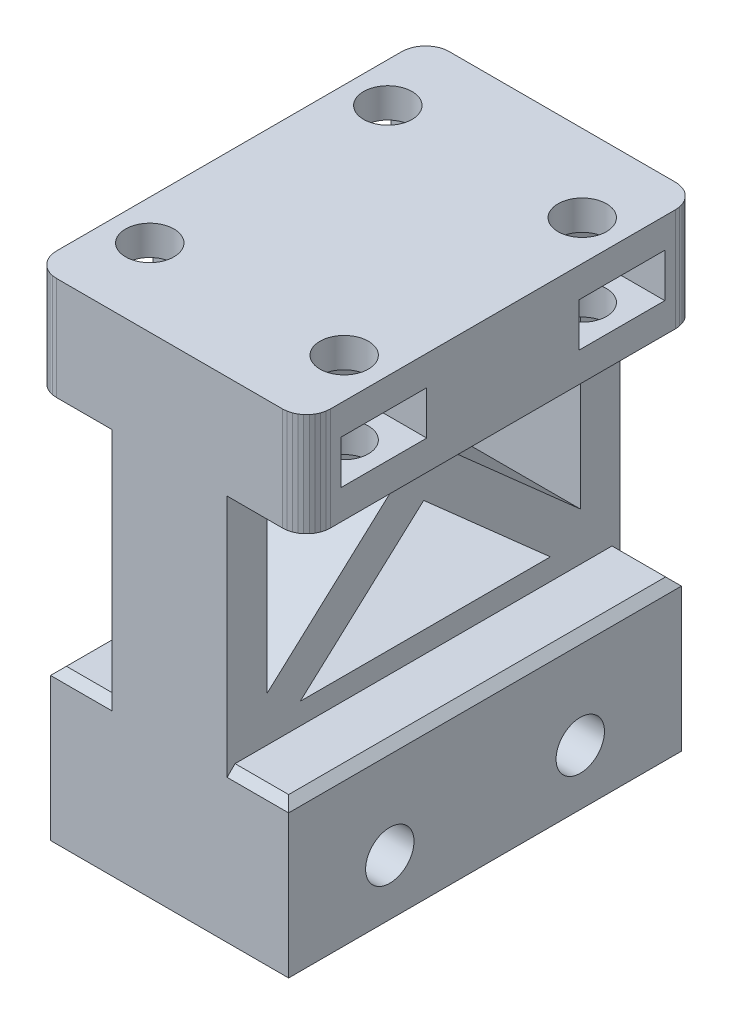
SolidWorks part; units mm, degrees
ref_plane "Front Plane" through (0, 0, 0) normal (0, 0, 1) x (1, 0, 0)
ref_plane "Top Plane" through (0, 0, 0) normal (0, 1, 0) x (1, 0, 0)
ref_plane "Right Plane" through (0, 0, 0) normal (1, 0, 0) x (0, 0, -1)
ref_plane "Plane1" through (652.0422, 0, 0) normal (-1, 0, 0) x (0, -1, 0)
sketch "Sketch1" plane through (652.0422, 0, 0) normal (-1, 0, 0) x (0, -1, 0)
  line L0 (-861.9581, 1249.6927) -> (-861.9581, 1289.1927)
  line L1 (-861.9581, 1289.1927) -> (-876.5101, 1273.1855)
  line L2 (-876.5101, 1273.1855) -> (-886.034, 1283.9338)
  line L3 (-886.034, 1283.9338) -> (-886.034, 1255.2762)
  line L4 (-886.034, 1255.2762) -> (-876.5578, 1265.7)
  line L5 (-876.5578, 1265.7) -> (-862.3742, 1249.6927)
  line L6 (-862.3742, 1249.6927) -> (-861.9581, 1249.6927)
extrude "Boss-Extrude1" add sketch "Sketch1" against normal blind 14.5
sketch "Sketch2" plane through (0, 861.9581, 0) normal (0, -1, 0) x (1, 0, 0)
  line L0 (652.0422, 1249.6927) -> (652.0422, 1289.1927)
  line L1 (652.0422, 1289.1927) -> (666.5421, 1289.1927)
  line L2 (666.5421, 1289.1927) -> (666.5421, 1249.6927)
  line L3 (666.5421, 1249.6927) -> (652.0422, 1249.6927)
extrude "Boss-Extrude2" add sketch "Sketch2" along normal blind 25.6425
sketch "Sketch3" plane through (0, 0, 1249.6927) normal (0, 0, -1) x (-1, 0, 0)
  line L0 (-652.0422, 886.034) -> (-652.0422, 836.3156)
  line L1 (-652.0422, 836.3156) -> (-666.5421, 836.3156)
  line L2 (-666.5421, 836.3156) -> (-666.5421, 886.034)
  line L3 (-666.5421, 886.034) -> (-652.0422, 886.034)
extrude "Boss-Extrude3" add sketch "Sketch3" along normal blind 5
sketch "Sketch4" plane through (0, 0, 1289.1927) normal (0, 0, 1) x (1, 0, 0)
  line L0 (652.0422, 886.034) -> (666.5421, 886.034)
  line L1 (666.5421, 886.034) -> (666.5421, 836.3156)
  line L2 (666.5421, 836.3156) -> (652.0422, 836.3156)
  line L3 (652.0422, 836.3156) -> (652.0422, 886.034)
extrude "Boss-Extrude4" add sketch "Sketch4" along normal blind 5
sketch "Sketch5" plane through (0, 886.034, 0) normal (0, 1, 0) x (-1, 0, 0)
  line L0 (-642.744, 1245.7644) -> (-643.1137, 1245.3946)
  line L1 (-643.1137, 1245.3946) -> (-643.5421, 1245.0947)
  line L2 (-643.5421, 1245.0947) -> (-644.0161, 1244.8736)
  line L3 (-644.0161, 1244.8736) -> (-644.5212, 1244.7383)
  line L4 (-644.5212, 1244.7383) -> (-645.0421, 1244.6927)
  line L5 (-645.0421, 1244.6927) -> (-673.5421, 1244.6927)
  line L6 (-673.5421, 1244.6927) -> (-674.0631, 1244.7383)
  line L7 (-674.0631, 1244.7383) -> (-674.5682, 1244.8736)
  line L8 (-674.5682, 1244.8736) -> (-675.0422, 1245.0947)
  line L9 (-675.0422, 1245.0947) -> (-675.4705, 1245.3946)
  line L10 (-675.4705, 1245.3946) -> (-675.8403, 1245.7644)
  line L11 (-675.8403, 1245.7644) -> (-676.1402, 1246.1927)
  line L12 (-676.1402, 1246.1927) -> (-676.3612, 1246.6667)
  line L13 (-676.3612, 1246.6667) -> (-676.4966, 1247.1718)
  line L14 (-676.4966, 1247.1718) -> (-676.5421, 1247.6927)
  line L15 (-676.5421, 1247.6927) -> (-676.5421, 1291.1927)
  line L16 (-676.5421, 1291.1927) -> (-676.4966, 1291.7136)
  line L17 (-676.4966, 1291.7136) -> (-676.3612, 1292.2187)
  line L18 (-676.3612, 1292.2187) -> (-676.1402, 1292.6927)
  line L19 (-676.1402, 1292.6927) -> (-675.8403, 1293.1211)
  line L20 (-675.8403, 1293.1211) -> (-675.4705, 1293.4908)
  line L21 (-675.4705, 1293.4908) -> (-675.0422, 1293.7908)
  line L22 (-675.0422, 1293.7908) -> (-674.5682, 1294.0117)
  line L23 (-674.5682, 1294.0117) -> (-674.0631, 1294.1471)
  line L24 (-674.0631, 1294.1471) -> (-673.5421, 1294.1927)
  line L25 (-673.5421, 1294.1927) -> (-645.0421, 1294.1927)
  line L26 (-645.0421, 1294.1927) -> (-644.5212, 1294.1471)
  line L27 (-644.5212, 1294.1471) -> (-644.0161, 1294.0117)
  line L28 (-644.0161, 1294.0117) -> (-643.5421, 1293.7908)
  line L29 (-643.5421, 1293.7908) -> (-643.1137, 1293.4908)
  line L30 (-643.1137, 1293.4908) -> (-642.744, 1293.1211)
  line L31 (-642.744, 1293.1211) -> (-642.4441, 1292.6927)
  line L32 (-642.4441, 1292.6927) -> (-642.2231, 1292.2187)
  line L33 (-642.2231, 1292.2187) -> (-642.0877, 1291.7136)
  line L34 (-642.0877, 1291.7136) -> (-642.0421, 1291.1927)
  line L35 (-642.0421, 1291.1927) -> (-642.0421, 1247.6927)
  line L36 (-642.0421, 1247.6927) -> (-642.0877, 1247.1718)
  line L37 (-642.0877, 1247.1718) -> (-642.2231, 1246.6667)
  line L38 (-642.2231, 1246.6667) -> (-642.4441, 1246.1927)
  line L39 (-642.4441, 1246.1927) -> (-642.744, 1245.7644)
extrude "Boss-Extrude5" add sketch "Sketch5" along normal blind 13
sketch "Sketch6" plane through (652.0422, 0, 0) normal (-1, 0, 0) x (0, 0, 1)
  line L0 (1244.6927, 836.3156) -> (1244.6927, 856.334)
  line L1 (1244.6927, 856.334) -> (1294.1927, 856.334)
  line L2 (1294.1927, 856.334) -> (1294.1927, 836.3156)
  line L3 (1294.1927, 836.3156) -> (1244.6927, 836.3156)
extrude "Boss-Extrude6" add sketch "Sketch6" along normal blind 7.75
sketch "Sketch7" plane through (666.5421, 0, 0) normal (1, 0, 0) x (0, 0, -1)
  line L0 (-1294.1927, 836.3156) -> (-1294.1927, 856.334)
  line L1 (-1294.1927, 856.334) -> (-1244.6927, 856.334)
  line L2 (-1244.6927, 856.334) -> (-1244.6927, 836.3156)
  line L3 (-1244.6927, 836.3156) -> (-1294.1927, 836.3156)
extrude "Boss-Extrude7" add sketch "Sketch7" along normal blind 7.75
ref_plane "Plane2" through (0, 889.784, 0) normal (0, -1, 0) x (1, 0, 0)
sketch "Sketch8" plane through (0, 889.784, 0) normal (0, -1, 0) x (1, 0, 0)
  line L0 (676.5421, 1259.8467) -> (668.4221, 1259.8467)
  line L1 (668.4221, 1259.8467) -> (665.3021, 1254.4427)
  line L2 (665.3021, 1254.4427) -> (668.4221, 1249.0387)
  line L3 (668.4221, 1249.0387) -> (676.5421, 1249.0387)
  line L4 (676.5421, 1249.0387) -> (676.5421, 1259.8467)
extrude "Cut-Extrude1" cut sketch "Sketch8" against normal blind 5.5
sketch "Sketch9" plane through (0, 899.034, 0) normal (0, 1, 0) x (-1, 0, 0)
  line L0 (-672.0718, 1251.439) -> (-671.5421, 1251.3927) construction
  line L1 (-671.5421, 1251.3927) -> (-671.0125, 1251.439) construction
  line L2 (-671.0125, 1251.439) -> (-670.499, 1251.5767) construction
  line L3 (-670.499, 1251.5767) -> (-670.0171, 1251.8013) construction
  line L4 (-670.0171, 1251.8013) -> (-669.5817, 1252.1062) construction
  line L5 (-669.5817, 1252.1062) -> (-669.2057, 1252.4822) construction
  line L6 (-669.2057, 1252.4822) -> (-668.9007, 1252.9176) construction
  line L7 (-668.9007, 1252.9176) -> (-668.6761, 1253.3995) construction
  line L8 (-668.6761, 1253.3995) -> (-668.5385, 1253.913) construction
  line L9 (-668.5385, 1253.913) -> (-668.4921, 1254.4427) construction
  line L10 (-668.4921, 1254.4427) -> (-668.5385, 1254.9723) construction
  line L11 (-668.5385, 1254.9723) -> (-668.6761, 1255.4859) construction
  line L12 (-668.6761, 1255.4859) -> (-668.9007, 1255.9677) construction
  line L13 (-668.9007, 1255.9677) -> (-669.2057, 1256.4032) construction
  line L14 (-669.2057, 1256.4032) -> (-669.5817, 1256.7791) construction
  line L15 (-669.5817, 1256.7791) -> (-670.0171, 1257.084) construction
  line L16 (-670.0171, 1257.084) -> (-670.499, 1257.3087) construction
  line L17 (-670.499, 1257.3087) -> (-671.0125, 1257.4463) construction
  line L18 (-671.0125, 1257.4463) -> (-671.5421, 1257.4927) construction
  line L19 (-671.5421, 1257.4927) -> (-672.0718, 1257.4463) construction
  line L20 (-672.0718, 1257.4463) -> (-672.5853, 1257.3087) construction
  line L21 (-672.5853, 1257.3087) -> (-673.0672, 1257.084) construction
  line L22 (-673.0672, 1257.084) -> (-673.5026, 1256.7791) construction
  line L23 (-673.5026, 1256.7791) -> (-673.8786, 1256.4032) construction
  line L24 (-673.8786, 1256.4032) -> (-674.1835, 1255.9677) construction
  line L25 (-674.1835, 1255.9677) -> (-674.4082, 1255.4859) construction
  line L26 (-674.4082, 1255.4859) -> (-674.5458, 1254.9723) construction
  line L27 (-674.5458, 1254.9723) -> (-674.5921, 1254.4427) construction
  line L28 (-674.5921, 1254.4427) -> (-674.5458, 1253.913) construction
  line L29 (-674.5458, 1253.913) -> (-674.4082, 1253.3995) construction
  line L30 (-674.4082, 1253.3995) -> (-674.1835, 1252.9176) construction
  line L31 (-674.1835, 1252.9176) -> (-673.8786, 1252.4822) construction
  line L32 (-673.8786, 1252.4822) -> (-673.5026, 1252.1062) construction
  line L33 (-673.5026, 1252.1062) -> (-673.0672, 1251.8013) construction
  line L34 (-673.0672, 1251.8013) -> (-672.5853, 1251.5767) construction
  line L35 (-672.5853, 1251.5767) -> (-672.0718, 1251.439) construction
  line L36 (-671.5421, 1251.3927) -> (-671.5421, 1257.4927) construction
  circle A0 centre (-671.5421, 1254.4427) radius 3.05
extrude "Cut-Extrude2" cut sketch "Sketch9" against normal up to surface (13 mm away)
sketch "Sketch10" plane through (0, 889.784, 0) normal (0, -1, 0) x (1, 0, 0)
  line L0 (642.0421, 1249.0387) -> (650.1621, 1249.0387)
  line L1 (650.1621, 1249.0387) -> (653.2821, 1254.4427)
  line L2 (653.2821, 1254.4427) -> (650.1621, 1259.8467)
  line L3 (650.1621, 1259.8467) -> (642.0421, 1259.8467)
  line L4 (642.0421, 1259.8467) -> (642.0421, 1249.0387)
extrude "Cut-Extrude3" cut sketch "Sketch10" against normal blind 5.5
sketch "Sketch11" plane through (0, 899.034, 0) normal (0, 1, 0) x (-1, 0, 0)
  line L0 (-647.5717, 1257.4463) -> (-648.0852, 1257.3087) construction
  line L1 (-648.0852, 1257.3087) -> (-648.5671, 1257.084) construction
  line L2 (-648.5671, 1257.084) -> (-649.0026, 1256.7791) construction
  line L3 (-649.0026, 1256.7791) -> (-649.3785, 1256.4032) construction
  line L4 (-649.3785, 1256.4032) -> (-649.6835, 1255.9677) construction
  line L5 (-649.6835, 1255.9677) -> (-649.9082, 1255.4859) construction
  line L6 (-649.9082, 1255.4859) -> (-650.0458, 1254.9723) construction
  line L7 (-650.0458, 1254.9723) -> (-650.0921, 1254.4427) construction
  line L8 (-650.0921, 1254.4427) -> (-650.0458, 1253.913) construction
  line L9 (-650.0458, 1253.913) -> (-649.9082, 1253.3995) construction
  line L10 (-649.9082, 1253.3995) -> (-649.6835, 1252.9176) construction
  line L11 (-649.6835, 1252.9176) -> (-649.3785, 1252.4822) construction
  line L12 (-649.3785, 1252.4822) -> (-649.0026, 1252.1062) construction
  line L13 (-649.0026, 1252.1062) -> (-648.5671, 1251.8013) construction
  line L14 (-648.5671, 1251.8013) -> (-648.0852, 1251.5767) construction
  line L15 (-648.0852, 1251.5767) -> (-647.5717, 1251.439) construction
  line L16 (-647.5717, 1251.439) -> (-647.0421, 1251.3927) construction
  line L17 (-647.0421, 1251.3927) -> (-646.5125, 1251.439) construction
  line L18 (-646.5125, 1251.439) -> (-645.999, 1251.5767) construction
  line L19 (-645.999, 1251.5767) -> (-645.5171, 1251.8013) construction
  line L20 (-645.5171, 1251.8013) -> (-645.0816, 1252.1062) construction
  line L21 (-645.0816, 1252.1062) -> (-644.7057, 1252.4822) construction
  line L22 (-644.7057, 1252.4822) -> (-644.4008, 1252.9176) construction
  line L23 (-644.4008, 1252.9176) -> (-644.1761, 1253.3995) construction
  line L24 (-644.1761, 1253.3995) -> (-644.0384, 1253.913) construction
  line L25 (-644.0384, 1253.913) -> (-643.9921, 1254.4427) construction
  line L26 (-643.9921, 1254.4427) -> (-644.0384, 1254.9723) construction
  line L27 (-644.0384, 1254.9723) -> (-644.1761, 1255.4859) construction
  line L28 (-644.1761, 1255.4859) -> (-644.4008, 1255.9677) construction
  line L29 (-644.4008, 1255.9677) -> (-644.7057, 1256.4032) construction
  line L30 (-644.7057, 1256.4032) -> (-645.0816, 1256.7791) construction
  line L31 (-645.0816, 1256.7791) -> (-645.5171, 1257.084) construction
  line L32 (-645.5171, 1257.084) -> (-645.999, 1257.3087) construction
  line L33 (-645.999, 1257.3087) -> (-646.5125, 1257.4463) construction
  line L34 (-646.5125, 1257.4463) -> (-647.0421, 1257.4927) construction
  line L35 (-647.0421, 1257.4927) -> (-647.5717, 1257.4463) construction
  line L36 (-647.0421, 1251.3927) -> (-647.0421, 1257.4927) construction
  circle A0 centre (-647.0421, 1254.4427) radius 3.05
extrude "Cut-Extrude4" cut sketch "Sketch11" against normal up to surface (13 mm away) up to face at (671.5421, 886.034, 1251.3927)
sketch "Sketch12" plane through (0, 889.784, 0) normal (0, -1, 0) x (1, 0, 0)
  line L0 (642.0421, 1279.0387) -> (650.1621, 1279.0387)
  line L1 (650.1621, 1279.0387) -> (653.2821, 1284.4427)
  line L2 (653.2821, 1284.4427) -> (650.1621, 1289.8467)
  line L3 (650.1621, 1289.8467) -> (642.0421, 1289.8467)
  line L4 (642.0421, 1289.8467) -> (642.0421, 1279.0387)
extrude "Cut-Extrude5" cut sketch "Sketch12" against normal blind 5.5
sketch "Sketch13" plane through (0, 899.034, 0) normal (0, 1, 0) x (-1, 0, 0)
  line L0 (-644.0384, 1283.913) -> (-643.9921, 1284.4427) construction
  line L1 (-643.9921, 1284.4427) -> (-644.0384, 1284.9723) construction
  line L2 (-644.0384, 1284.9723) -> (-644.1761, 1285.4859) construction
  line L3 (-644.1761, 1285.4859) -> (-644.4008, 1285.9677) construction
  line L4 (-644.4008, 1285.9677) -> (-644.7057, 1286.4032) construction
  line L5 (-644.7057, 1286.4032) -> (-645.0816, 1286.7792) construction
  line L6 (-645.0816, 1286.7792) -> (-645.5171, 1287.0841) construction
  line L7 (-645.5171, 1287.0841) -> (-645.999, 1287.3087) construction
  line L8 (-645.999, 1287.3087) -> (-646.5125, 1287.4464) construction
  line L9 (-646.5125, 1287.4464) -> (-647.0421, 1287.4926) construction
  line L10 (-647.0421, 1287.4926) -> (-647.5717, 1287.4464) construction
  line L11 (-647.5717, 1287.4464) -> (-648.0852, 1287.3087) construction
  line L12 (-648.0852, 1287.3087) -> (-648.5671, 1287.0841) construction
  line L13 (-648.5671, 1287.0841) -> (-649.0026, 1286.7792) construction
  line L14 (-649.0026, 1286.7792) -> (-649.3785, 1286.4032) construction
  line L15 (-649.3785, 1286.4032) -> (-649.6835, 1285.9677) construction
  line L16 (-649.6835, 1285.9677) -> (-649.9082, 1285.4859) construction
  line L17 (-649.9082, 1285.4859) -> (-650.0458, 1284.9723) construction
  line L18 (-650.0458, 1284.9723) -> (-650.0921, 1284.4427) construction
  line L19 (-650.0921, 1284.4427) -> (-650.0458, 1283.913) construction
  line L20 (-650.0458, 1283.913) -> (-649.9082, 1283.3995) construction
  line L21 (-649.9082, 1283.3995) -> (-649.6835, 1282.9177) construction
  line L22 (-649.6835, 1282.9177) -> (-649.3785, 1282.4821) construction
  line L23 (-649.3785, 1282.4821) -> (-649.0026, 1282.1063) construction
  line L24 (-649.0026, 1282.1063) -> (-648.5671, 1281.8013) construction
  line L25 (-648.5671, 1281.8013) -> (-648.0852, 1281.5766) construction
  line L26 (-648.0852, 1281.5766) -> (-647.5717, 1281.4391) construction
  line L27 (-647.5717, 1281.4391) -> (-647.0421, 1281.3927) construction
  line L28 (-647.0421, 1281.3927) -> (-646.5125, 1281.4391) construction
  line L29 (-646.5125, 1281.4391) -> (-645.999, 1281.5766) construction
  line L30 (-645.999, 1281.5766) -> (-645.5171, 1281.8013) construction
  line L31 (-645.5171, 1281.8013) -> (-645.0816, 1282.1063) construction
  line L32 (-645.0816, 1282.1063) -> (-644.7057, 1282.4821) construction
  line L33 (-644.7057, 1282.4821) -> (-644.4008, 1282.9177) construction
  line L34 (-644.4008, 1282.9177) -> (-644.1761, 1283.3995) construction
  line L35 (-644.1761, 1283.3995) -> (-644.0384, 1283.913) construction
  line L36 (-647.0421, 1287.4926) -> (-647.0421, 1281.3927) construction
  circle A0 centre (-647.0421, 1284.4427) radius 3.05
extrude "Cut-Extrude6" cut sketch "Sketch13" against normal up to surface (13 mm away) up to face at (647.0421, 886.034, 1251.3927)
sketch "Sketch14" plane through (0, 889.784, 0) normal (0, -1, 0) x (1, 0, 0)
  line L0 (676.5421, 1289.8467) -> (668.4221, 1289.8467)
  line L1 (668.4221, 1289.8467) -> (665.3021, 1284.4427)
  line L2 (665.3021, 1284.4427) -> (668.4221, 1279.0387)
  line L3 (668.4221, 1279.0387) -> (676.5421, 1279.0387)
  line L4 (676.5421, 1279.0387) -> (676.5421, 1289.8467)
extrude "Cut-Extrude7" cut sketch "Sketch14" against normal blind 5.5
sketch "Sketch15" plane through (0, 899.034, 0) normal (0, 1, 0) x (-1, 0, 0)
  line L0 (-673.5026, 1286.7792) -> (-673.8786, 1286.4032) construction
  line L1 (-673.8786, 1286.4032) -> (-674.1835, 1285.9677) construction
  line L2 (-674.1835, 1285.9677) -> (-674.4082, 1285.4859) construction
  line L3 (-674.4082, 1285.4859) -> (-674.5458, 1284.9723) construction
  line L4 (-674.5458, 1284.9723) -> (-674.5921, 1284.4427) construction
  line L5 (-674.5921, 1284.4427) -> (-674.5458, 1283.913) construction
  line L6 (-674.5458, 1283.913) -> (-674.4082, 1283.3995) construction
  line L7 (-674.4082, 1283.3995) -> (-674.1835, 1282.9177) construction
  line L8 (-674.1835, 1282.9177) -> (-673.8786, 1282.4821) construction
  line L9 (-673.8786, 1282.4821) -> (-673.5026, 1282.1063) construction
  line L10 (-673.5026, 1282.1063) -> (-673.0672, 1281.8013) construction
  line L11 (-673.0672, 1281.8013) -> (-672.5853, 1281.5766) construction
  line L12 (-672.5853, 1281.5766) -> (-672.0718, 1281.4391) construction
  line L13 (-672.0718, 1281.4391) -> (-671.5421, 1281.3927) construction
  line L14 (-671.5421, 1281.3927) -> (-671.0125, 1281.4391) construction
  line L15 (-671.0125, 1281.4391) -> (-670.499, 1281.5766) construction
  line L16 (-670.499, 1281.5766) -> (-670.0171, 1281.8013) construction
  line L17 (-670.0171, 1281.8013) -> (-669.5817, 1282.1063) construction
  line L18 (-669.5817, 1282.1063) -> (-669.2057, 1282.4821) construction
  line L19 (-669.2057, 1282.4821) -> (-668.9007, 1282.9177) construction
  line L20 (-668.9007, 1282.9177) -> (-668.6761, 1283.3995) construction
  line L21 (-668.6761, 1283.3995) -> (-668.5385, 1283.913) construction
  line L22 (-668.5385, 1283.913) -> (-668.4921, 1284.4427) construction
  line L23 (-668.4921, 1284.4427) -> (-668.5385, 1284.9723) construction
  line L24 (-668.5385, 1284.9723) -> (-668.6761, 1285.4859) construction
  line L25 (-668.6761, 1285.4859) -> (-668.9007, 1285.9677) construction
  line L26 (-668.9007, 1285.9677) -> (-669.2057, 1286.4032) construction
  line L27 (-669.2057, 1286.4032) -> (-669.5817, 1286.7792) construction
  line L28 (-669.5817, 1286.7792) -> (-670.0171, 1287.0841) construction
  line L29 (-670.0171, 1287.0841) -> (-670.499, 1287.3087) construction
  line L30 (-670.499, 1287.3087) -> (-671.0125, 1287.4464) construction
  line L31 (-671.0125, 1287.4464) -> (-671.5421, 1287.4926) construction
  line L32 (-671.5421, 1287.4926) -> (-672.0718, 1287.4464) construction
  line L33 (-672.0718, 1287.4464) -> (-672.5853, 1287.3087) construction
  line L34 (-672.5853, 1287.3087) -> (-673.0672, 1287.0841) construction
  line L35 (-673.0672, 1287.0841) -> (-673.5026, 1286.7792) construction
  line L36 (-671.5421, 1287.4926) -> (-671.5421, 1281.3927) construction
  circle A0 centre (-671.5421, 1284.4427) radius 3.05
extrude "Cut-Extrude8" cut sketch "Sketch15" against normal up to surface (13 mm away) up to face at (647.0421, 886.034, 1281.3927)
sketch "Sketch16" plane through (644.2921, 0, 0) normal (-1, 0, 0) x (0, 0, 1)
  line L0 (1281.9723, 847.3376) -> (1281.4426, 847.384) construction
  line L1 (1281.4426, 847.384) -> (1280.9131, 847.3376) construction
  line L2 (1280.9131, 847.3376) -> (1280.3996, 847.2) construction
  line L3 (1280.3996, 847.2) -> (1279.9177, 846.9753) construction
  line L4 (1279.9177, 846.9753) -> (1279.4821, 846.6704) construction
  line L5 (1279.4821, 846.6704) -> (1279.1063, 846.2945) construction
  line L6 (1279.1063, 846.2945) -> (1278.8013, 845.8589) construction
  line L7 (1278.8013, 845.8589) -> (1278.5766, 845.3771) construction
  line L8 (1278.5766, 845.3771) -> (1278.439, 844.8636) construction
  line L9 (1278.439, 844.8636) -> (1278.3927, 844.3339) construction
  line L10 (1278.3927, 844.3339) -> (1278.439, 843.8044) construction
  line L11 (1278.439, 843.8044) -> (1278.5766, 843.2908) construction
  line L12 (1278.5766, 843.2908) -> (1278.8013, 842.809) construction
  line L13 (1278.8013, 842.809) -> (1279.1063, 842.3734) construction
  line L14 (1279.1063, 842.3734) -> (1279.4821, 841.9975) construction
  line L15 (1279.4821, 841.9975) -> (1279.9177, 841.6926) construction
  line L16 (1279.9177, 841.6926) -> (1280.3996, 841.4679) construction
  line L17 (1280.3996, 841.4679) -> (1280.9131, 841.3303) construction
  line L18 (1280.9131, 841.3303) -> (1281.4426, 841.284) construction
  line L19 (1281.4426, 841.284) -> (1281.9723, 841.3303) construction
  line L20 (1281.9723, 841.3303) -> (1282.4858, 841.4679) construction
  line L21 (1282.4858, 841.4679) -> (1282.9677, 841.6926) construction
  line L22 (1282.9677, 841.6926) -> (1283.4032, 841.9975) construction
  line L23 (1283.4032, 841.9975) -> (1283.7791, 842.3734) construction
  line L24 (1283.7791, 842.3734) -> (1284.0841, 842.809) construction
  line L25 (1284.0841, 842.809) -> (1284.3088, 843.2908) construction
  line L26 (1284.3088, 843.2908) -> (1284.4464, 843.8044) construction
  line L27 (1284.4464, 843.8044) -> (1284.4927, 844.3339) construction
  line L28 (1284.4927, 844.3339) -> (1284.4464, 844.8636) construction
  line L29 (1284.4464, 844.8636) -> (1284.3088, 845.3771) construction
  line L30 (1284.3088, 845.3771) -> (1284.0841, 845.8589) construction
  line L31 (1284.0841, 845.8589) -> (1283.7791, 846.2945) construction
  line L32 (1283.7791, 846.2945) -> (1283.4032, 846.6704) construction
  line L33 (1283.4032, 846.6704) -> (1282.9677, 846.9753) construction
  line L34 (1282.9677, 846.9753) -> (1282.4858, 847.2) construction
  line L35 (1282.4858, 847.2) -> (1281.9723, 847.3376) construction
  line L36 (1281.4426, 841.284) -> (1281.4426, 847.384) construction
  circle A0 centre (1281.4426, 844.334) radius 3.05
extrude "Cut-Extrude9" cut sketch "Sketch16" against normal through all
sketch "Sketch17" plane through (674.2921, 0, 0) normal (1, 0, 0) x (0, 0, -1)
  line L0 (-1258.9676, 841.6926) -> (-1258.4858, 841.4679) construction
  line L1 (-1258.4858, 841.4679) -> (-1257.9724, 841.3303) construction
  line L2 (-1257.9724, 841.3303) -> (-1257.4427, 841.284) construction
  line L3 (-1257.4427, 841.284) -> (-1256.9131, 841.3303) construction
  line L4 (-1256.9131, 841.3303) -> (-1256.3995, 841.4679) construction
  line L5 (-1256.3995, 841.4679) -> (-1255.9177, 841.6926) construction
  line L6 (-1255.9177, 841.6926) -> (-1255.4822, 841.9975) construction
  line L7 (-1255.4822, 841.9975) -> (-1255.1062, 842.3734) construction
  line L8 (-1255.1062, 842.3734) -> (-1254.8013, 842.809) construction
  line L9 (-1254.8013, 842.809) -> (-1254.5766, 843.2908) construction
  line L10 (-1254.5766, 843.2908) -> (-1254.439, 843.8044) construction
  line L11 (-1254.439, 843.8044) -> (-1254.3926, 844.3339) construction
  line L12 (-1254.3926, 844.3339) -> (-1254.439, 844.8636) construction
  line L13 (-1254.439, 844.8636) -> (-1254.5766, 845.3771) construction
  line L14 (-1254.5766, 845.3771) -> (-1254.8013, 845.8589) construction
  line L15 (-1254.8013, 845.8589) -> (-1255.1062, 846.2945) construction
  line L16 (-1255.1062, 846.2945) -> (-1255.4822, 846.6704) construction
  line L17 (-1255.4822, 846.6704) -> (-1255.9177, 846.9753) construction
  line L18 (-1255.9177, 846.9753) -> (-1256.3995, 847.2) construction
  line L19 (-1256.3995, 847.2) -> (-1256.9131, 847.3376) construction
  line L20 (-1256.9131, 847.3376) -> (-1257.4427, 847.384) construction
  line L21 (-1257.4427, 847.384) -> (-1257.9724, 847.3376) construction
  line L22 (-1257.9724, 847.3376) -> (-1258.4858, 847.2) construction
  line L23 (-1258.4858, 847.2) -> (-1258.9676, 846.9753) construction
  line L24 (-1258.9676, 846.9753) -> (-1259.4032, 846.6704) construction
  line L25 (-1259.4032, 846.6704) -> (-1259.7791, 846.2945) construction
  line L26 (-1259.7791, 846.2945) -> (-1260.084, 845.8589) construction
  line L27 (-1260.084, 845.8589) -> (-1260.3087, 845.3771) construction
  line L28 (-1260.3087, 845.3771) -> (-1260.4463, 844.8636) construction
  line L29 (-1260.4463, 844.8636) -> (-1260.4927, 844.3339) construction
  line L30 (-1260.4927, 844.3339) -> (-1260.4463, 843.8044) construction
  line L31 (-1260.4463, 843.8044) -> (-1260.3087, 843.2908) construction
  line L32 (-1260.3087, 843.2908) -> (-1260.084, 842.809) construction
  line L33 (-1260.084, 842.809) -> (-1259.7791, 842.3734) construction
  line L34 (-1259.7791, 842.3734) -> (-1259.4032, 841.9975) construction
  line L35 (-1259.4032, 841.9975) -> (-1258.9676, 841.6926) construction
  line L36 (-1257.4427, 841.284) -> (-1257.4427, 847.384) construction
  circle A0 centre (-1257.4427, 844.334) radius 3.05
extrude "Cut-Extrude10" cut sketch "Sketch17" against normal through all
sketch "Sketch22" plane through (666.5421, 0, 0) normal (1, 0, 0) x (0, 0, -1)
  line L0 (-1253.4623, 859.0339) -> (-1269.4212, 873.1748)
  line L1 (-1269.4212, 873.1748) -> (-1284.9761, 859.0339)
  line L2 (-1284.9761, 859.0339) -> (-1253.4623, 859.0339)
extrude "Cut-Extrude15" cut sketch "Sketch22" against normal through all
chamfer "Chamfer1" distance 1 angle 44.998 6 edges at (670.4171, 856.334, 1244.6927) (670.4171, 856.334, 1294.1927) (674.2921, 856.334, 1269.4427) (648.1671, 856.334, 1244.6927) (644.2921, 856.334, 1269.4427) (648.1671, 856.334, 1294.1927)
chamfer "Chamfer2" distance 1 angle 45 4 edges at (659.2921, 836.3156, 1244.6927) (674.2921, 836.3156, 1269.4427) (644.2921, 836.3156, 1269.4427) (659.2921, 836.3156, 1294.1927)
